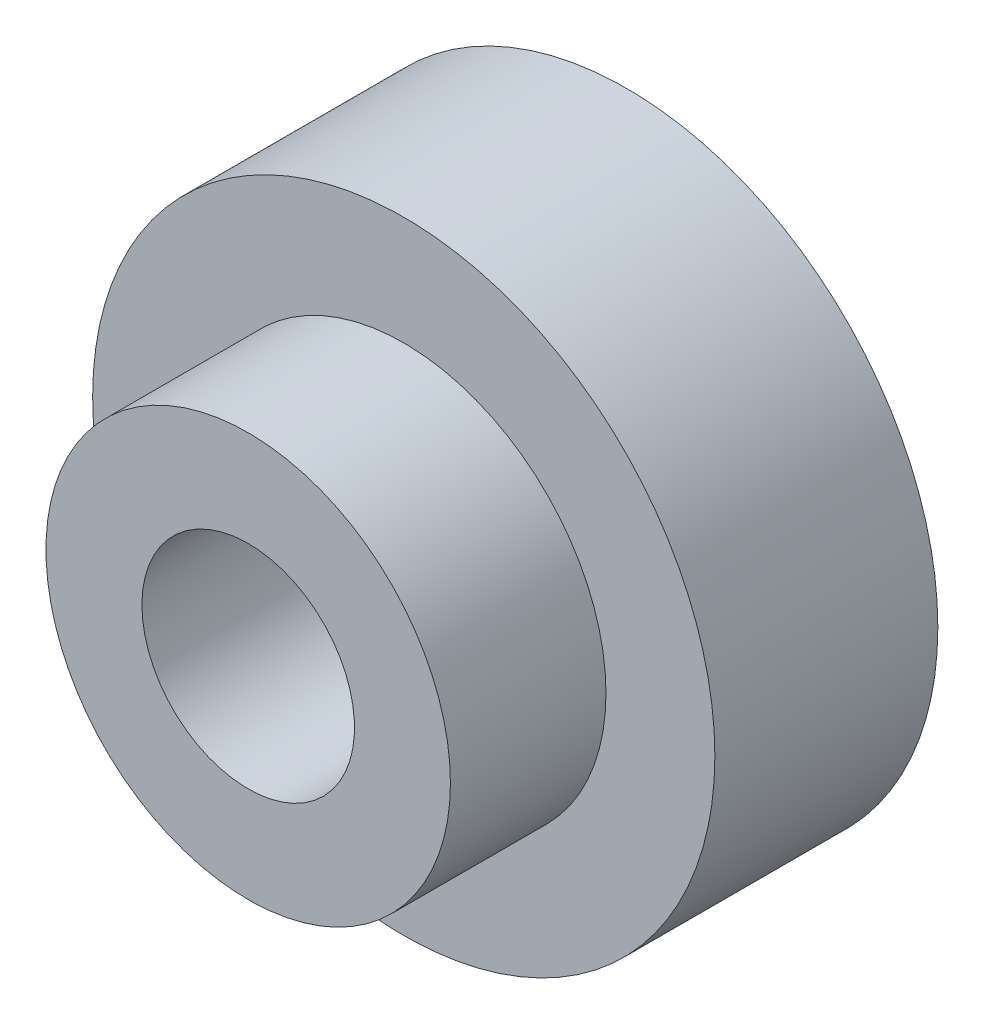
SolidWorks part; units mm, degrees
material "ABS PC"
ref_plane "Front Plane" through (0, 0, 0) normal (0, 0, 1) x (1, 0, 0)
ref_plane "Top Plane" through (0, 0, 0) normal (0, 1, 0) x (1, 0, 0)
ref_plane "Right Plane" through (0, 0, 0) normal (1, 0, 0) x (0, 0, -1)
sketch "Sketch1" plane through (0, 0, 0) normal (0, 0, 1) x (1, 0, 0)
  circle A0 centre (0, 0) radius 6
  circle A1 centre (0, 0) radius 2.05
  dimension "D1" = 12
  dimension "D2" = 4.1
extrude "Boss-Extrude1" add sketch "Sketch1" along normal blind 4.3
sketch "Sketch2" plane through (0, 0, 4.3) normal (0, 0, 1) x (1, 0, 0)
  circle A0 centre (0, 0) radius 2.05
  circle A1 centre (0, 0) radius 3.9
  dimension "D1" = 7.8
extrude "Boss-Extrude2" add sketch "Sketch2" along normal blind 3
